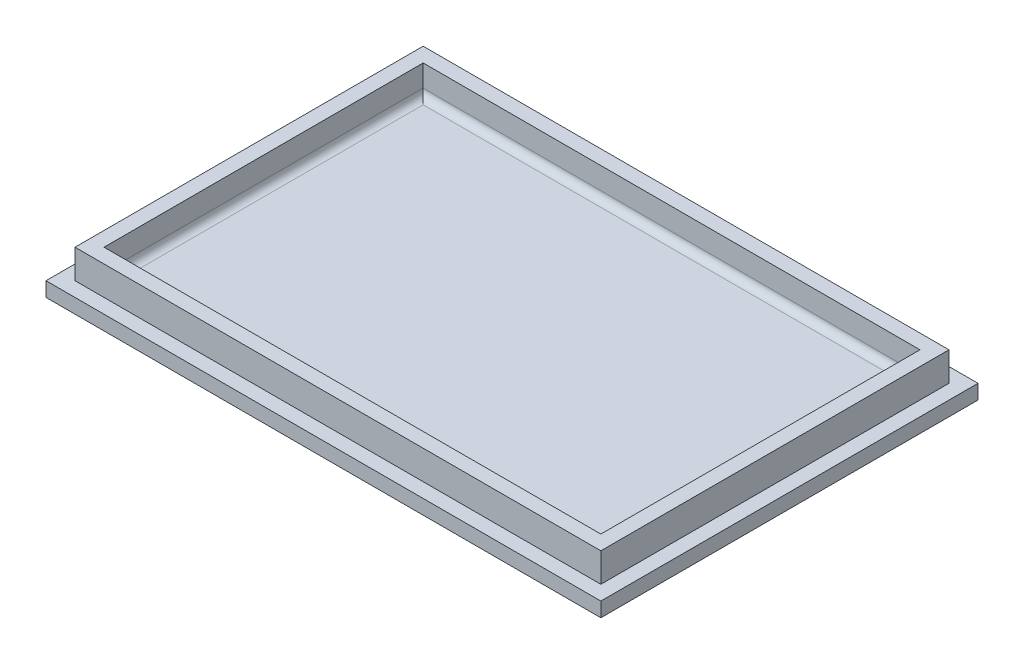
SolidWorks part; units mm, degrees
ref_plane "Front" through (0, 0, 0) normal (0, 0, 1) x (1, 0, 0)
ref_plane "Top" through (0, 0, 0) normal (0, 1, 0) x (1, 0, 0)
ref_plane "Right" through (0, 0, 0) normal (1, 0, 0) x (0, 0, -1)
sketch "Эскиз1" plane through (0, 0, 0) normal (0, 1, 0) x (1, 0, 0)
  line L1 (-54.8143, 27.6349) -> (21.6857, 27.6349)
  line L2 (-54.8143, 27.6349) -> (-54.8143, -24.3651)
  line L3 (-54.8143, -24.3651) -> (21.6857, -24.3651)
  line L4 (21.6857, 27.6349) -> (21.6857, -24.3651)
  dimension "D1" = 76.5
  dimension "D2" = 52
extrude "Бобышка-Вытянуть1" add sketch "Эскиз1" along normal blind 2
sketch "Эскиз2" plane through (0, 2, 0) normal (0, 1, 0) x (1, 0, 0)
  line L0 (-54.8143, 27.6349) -> (-54.8143, -24.3651) construction
  line L1 (-52.8143, 25.6349) -> (19.6857, 25.6349)
  line L2 (-52.8143, 25.6349) -> (-52.8143, -22.3651)
  line L3 (-52.8143, -22.3651) -> (19.6857, -22.3651)
  line L4 (19.6857, 25.6349) -> (19.6857, -22.3651)
  line L5 (21.6857, 27.6349) -> (-54.8143, 27.6349) construction
  line L6 (21.6857, -24.3651) -> (21.6857, 27.6349) construction
  line L7 (-54.8143, -24.3651) -> (21.6857, -24.3651) construction
  line L9 (-50.8143, 23.6349) -> (17.6857, 23.6349)
  line L10 (-50.8143, 23.6349) -> (-50.8143, -20.3651)
  line L11 (-50.8143, -20.3651) -> (17.6857, -20.3651)
  line L12 (17.6857, 23.6349) -> (17.6857, -20.3651)
  point P18 (-8.5805, -15.3651)
  dimension "D1" = 2
  dimension "D2" = 2
  dimension "D3" = 2
  dimension "D4" = 2
  dimension "D5" = 2
  dimension "D6" = 2
  dimension "D7" = 2
  dimension "D8" = 2
extrude "Бобышка-Вытянуть2" add sketch "Эскиз2" along normal blind 4
fillet "Скругление1" radius 1 4 edges at (-16.5643, 2, 20.3651) (-50.8143, 2, -1.6349) (17.6857, 2, -1.6349) (-16.5643, 2, -23.6349)
